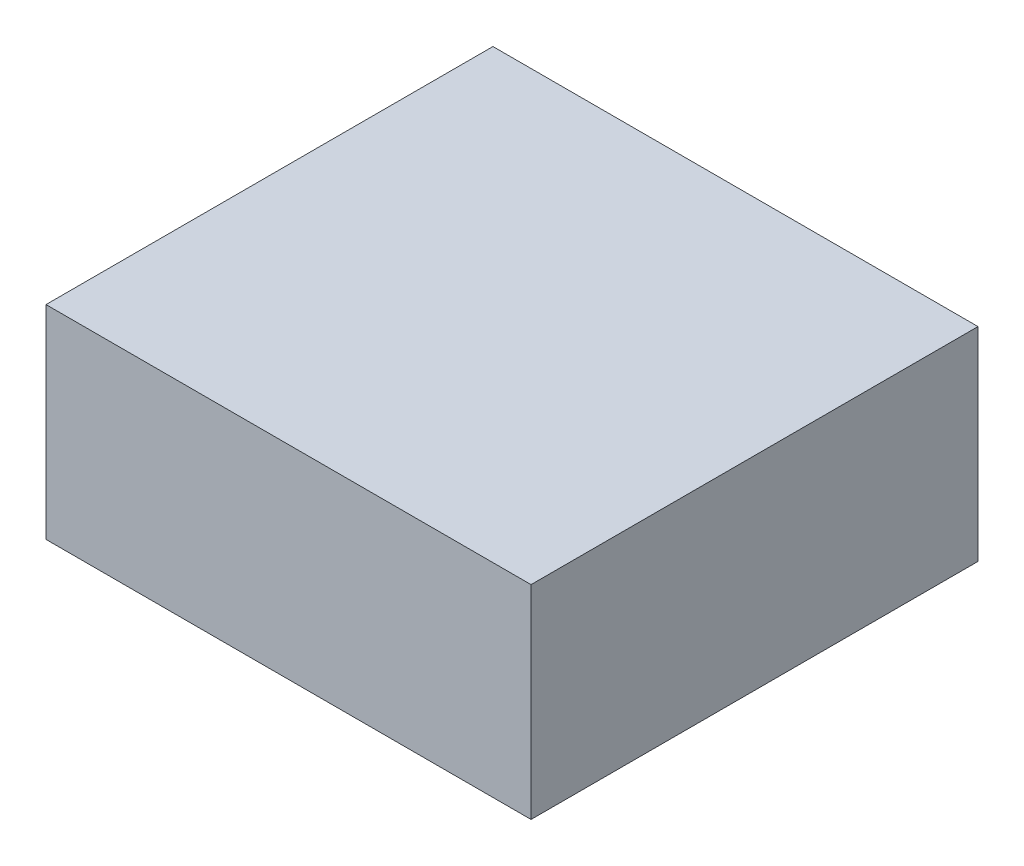
SolidWorks part; units mm, degrees
ref_plane "前视基准面" through (0, 0, 0) normal (0, 0, 1) x (1, 0, 0)
ref_plane "上视基准面" through (0, 0, 0) normal (0, 1, 0) x (1, 0, 0)
ref_plane "右视基准面" through (0, 0, 0) normal (1, 0, 0) x (0, 0, -1)
sketch "草图1" plane through (0, 0, 0) normal (0, 1, 0) x (1, 0, 0)
  line L1 (-90.551, 83.439) -> (90.551, 83.439)
  line L2 (-90.551, 83.439) -> (-90.551, -83.439)
  line L3 (-90.551, -83.439) -> (90.551, -83.439)
  line L4 (90.551, 83.439) -> (90.551, -83.439)
  line L5 (-90.551, 83.439) -> (90.551, -83.439) construction
  line L6 (-90.551, -83.439) -> (90.551, 83.439) construction
  point P0 (0, 0)
  dimension "D1" = 181.102
  dimension "D2" = 166.878
extrude "凸台-拉伸1" add sketch "草图1" along normal blind 75.946
